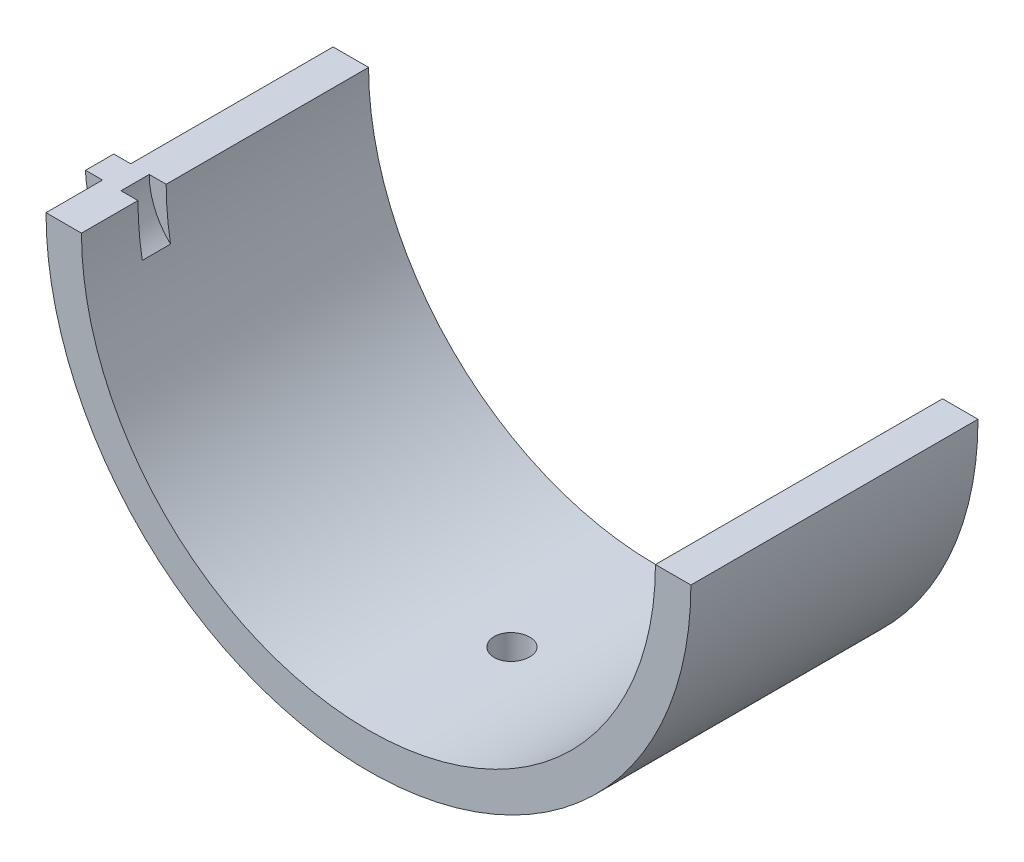
SolidWorks part; units mm, degrees
material "201 Annealed Stainless Steel (SS)"
ref_plane "Front Plane" through (0, 0, 0) normal (0, 0, 1) x (1, 0, 0)
ref_plane "Top Plane" through (0, 0, 0) normal (0, 1, 0) x (1, 0, 0)
ref_plane "Right Plane" through (0, 0, 0) normal (1, 0, 0) x (0, 0, -1)
sketch "Sketch1" plane through (0, 0, 0) normal (0, 0, 1) x (1, 0, 0)
  line L0 (0, 0) -> (0, 36.2585) construction
  line L1 (-36.2585, 36.2585) -> (-32.2707, 36.2585)
  line L2 (32.2707, 36.2585) -> (36.2585, 36.2585)
  circle A0 centre (0, 36.2585) radius 36.2585 construction
  circle A1 centre (0, 36.2585) radius 32.2707 construction
  arc A2 (-36.2585, 36.2585) -> (36.2585, 36.2585) centre (0, 36.2585) ccw
  arc A3 (32.2707, 36.2585) -> (-32.2707, 36.2585) centre (0, 36.2585) cw
  dimension "D1" = 3.9878
  dimension "D2" = 64.5414
extrude "Boss-Extrude1" add sketch "Sketch1" against normal blind 32.2834
sketch "Sketch2" plane through (0, 0, 0) normal (0, 1, 0) x (1, 0, 0)
  line L0 (0, 0) -> (0, 32.2834) construction
  line L1 (36.2585, 32.2834) -> (-36.2585, 32.2834) construction
  line L2 (36.2585, 16.1417) -> (-36.2585, 16.1417) construction
  line L3 (36.2585, 32.2834) -> (36.2585, 0) construction
  line L4 (-36.2585, 32.2834) -> (-36.2585, 0) construction
  circle A0 centre (0, 16.1417) radius 1.9939
  dimension "D1" = 3.9878
extrude "Cut-Extrude1" cut sketch "Sketch2" along normal up to next
ref_plane "Plane1" through (0, 0, -6.35) normal (0, 0, 1) x (1, 0, 0)
sketch "Sketch4" plane through (0, 0, -6.35) normal (0, 0, 1) x (1, 0, 0)
  line L0 (32.2707, 36.2585) -> (-32.2707, 36.2585) construction
  line L1 (36.2585, 36.2585) -> (38.1635, 36.2585) construction
  line L2 (38.1635, 36.2585) -> (38.1635, 39.4335) construction
  line L3 (0, 36.2585) -> (0, 0) construction
  line L4 (-36.2585, 36.2585) -> (-38.1635, 36.2585)
  arc A0 (36.2585, 36.2585) -> (35.8254, 30.6711) centre (0, 36.2585) cw construction
  arc A1 (35.8254, 30.6711) -> (38.1635, 36.2585) centre (30.3183, 36.2585) ccw
  arc A2 (-36.2585, 36.2585) -> (-35.8254, 30.6711) centre (0, 36.2585) ccw
  arc A3 (-35.8254, 30.6711) -> (-38.1635, 36.2585) centre (-30.3183, 36.2585) cw
  dimension "D1" = 3.175
  dimension "D2" = 1.905
extrude "Boss-Extrude2" add sketch "Sketch4" against normal blind 3.175 contours A2 A3 L4
sketch "Sketch5" plane through (0, 0, -6.35) normal (0, 0, 1) x (1, 0, 0)
  line L0 (32.2707, 36.2585) -> (-32.2707, 36.2585) construction
  line L1 (32.2707, 36.2585) -> (34.1757, 36.2585) construction
  line L2 (36.2585, 36.2585) -> (32.2707, 36.2585) construction
  line L3 (35.8254, 30.6711) -> (31.7833, 30.6711) construction
  line L5 (34.1757, 36.2585) -> (34.1757, 42.6085) construction
  line L6 (0, 36.2585) -> (0, 0) construction
  line L7 (-32.2707, 36.2585) -> (-34.1757, 36.2585)
  arc A0 (32.2707, 36.2585) -> (31.7833, 30.6711) centre (0, 36.2585) cw construction
  arc A1 (31.7833, 30.6711) -> (34.1757, 36.2585) centre (26.4549, 36.2585) ccw construction
  arc A2 (-32.2707, 36.2585) -> (-31.7833, 30.6711) centre (0, 36.2585) ccw
  arc A3 (-31.7833, 30.6711) -> (-34.1757, 36.2585) centre (-26.4549, 36.2585) cw
  dimension "D1" = 6.35
extrude "Cut-Extrude2" cut sketch "Sketch5" against normal blind 3.175 contours A3 L7 A2
sketch "Sketch6" [suppressed] plane through (0, 36.2585, 0) normal (0, 1, 0) x (1, 0, 0)
  line L0 (32.2707, 32.2834) -> (32.2707, 0) construction
  line L1 (32.2707, 16.1417) -> (31.3683, 16.1417) construction
  line L3 (32.2707, 17.9197) -> (32.2707, 14.3637)
  arc A0 (32.2707, 14.3637) -> (32.2707, 17.9197) centre (31.3683, 16.1417) ccw
  circle A1 centre (0, 16.1417) radius 1.9939 construction
  dimension "D1" = 3.556
  dimension "D2" = 0
ref_plane "Plane2" through (0, 0, -16.1417) normal (0, 0, 1) x (1, 0, 0)
sketch "Sketch8" plane through (0, 0, -16.1417) normal (0, 0, 1) x (1, 0, 0)
  line L2 (32.2707, 36.2585) -> (-32.2707, 36.2585) construction
  arc A0 (-32.2707, 36.2585) -> (32.2707, 36.2585) centre (0, 36.261) ccw
  dimension "D1" = 0.0025
sweep "Cut-Sweep1" [suppressed] cut profiles "Sketch6" path "Sketch8"
